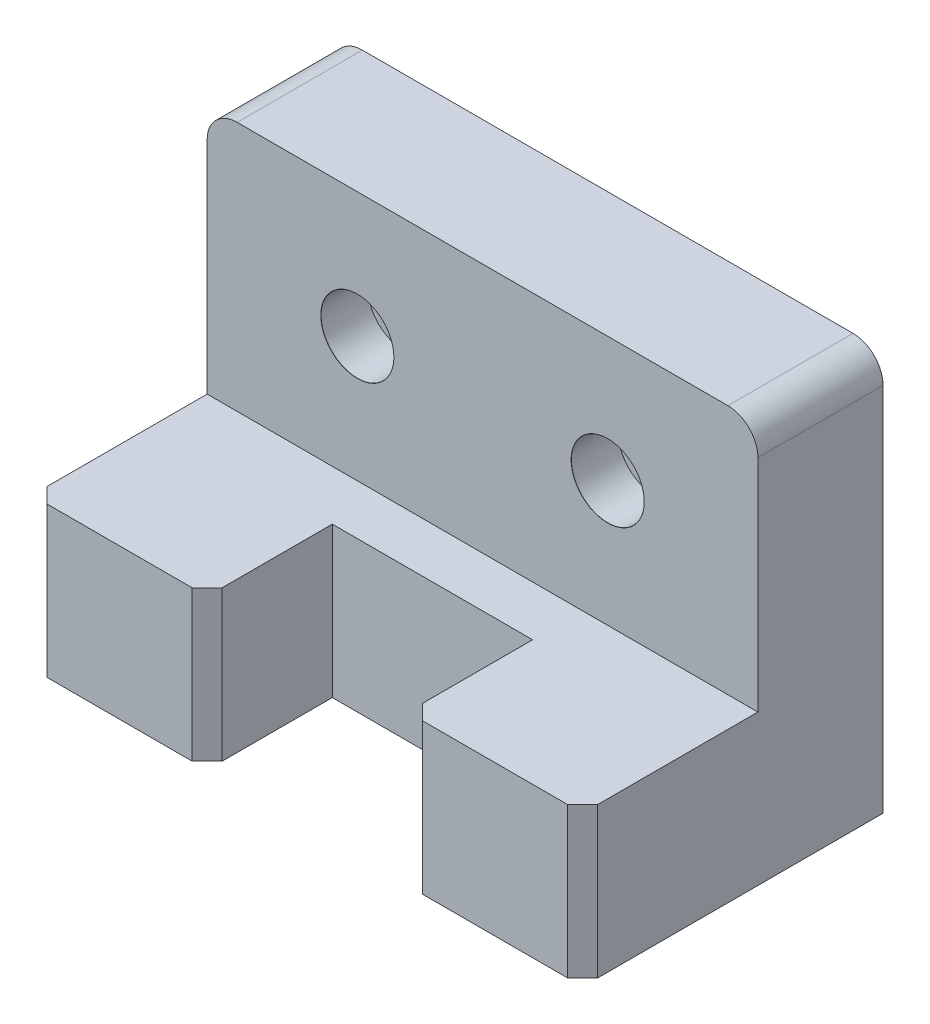
SolidWorks part; units mm, degrees
ref_plane "Front Plane" through (0, 0, 0) normal (0, 0, 1) x (1, 0, 0)
ref_plane "Top Plane" through (0, 0, 0) normal (0, 1, 0) x (1, 0, 0)
ref_plane "Right Plane" through (0, 0, 0) normal (1, 0, 0) x (0, 0, -1)
sketch "Sketch1" plane through (0, 0, 0) normal (0, 1, 0) x (1, 0, 0)
  line L0 (-20, -57) -> (-20, -35)
  line L1 (-55, 0) -> (55, 0)
  line L2 (-55, 0) -> (-55, -57)
  line L3 (-52, -60) -> (-23, -60)
  line L4 (55, 0) -> (55, -57)
  line L5 (-20, -35) -> (20, -35)
  line L6 (20, -35) -> (20, -57)
  line L7 (23, -60) -> (52, -60)
  line L8 (-55, -57) -> (-52, -60)
  line L9 (-23, -60) -> (-20, -57)
  line L10 (20, -57) -> (23, -60)
  line L11 (52, -60) -> (55, -57)
  point P1 (55, -60)
  point P2 (-55, -60)
  point P4 (-20, -60)
  point P9 (20, -60)
  dimension "D1" = 25
  dimension "D2" = 60
  dimension "D3" = 40
  dimension "D4" = 35
  dimension "D5" = 35
extrude "Boss-Extrude1" add sketch "Sketch1" along normal blind 80
sketch "Sketch2" plane through (0, 80, 0) normal (0, 1, 0) x (1, 0, 0)
  line L0 (55, 0) -> (-55, 0) construction
  line L1 (-64.3629, -25) -> (63.5311, -25)
  line L2 (-64.3629, -25) -> (-64.3629, -72.2064)
  line L3 (-64.3629, -72.2064) -> (63.5311, -72.2064)
  line L4 (63.5311, -25) -> (63.5311, -72.2064)
  dimension "D1" = 25
extrude "Cut-Extrude1" cut sketch "Sketch2" against normal offset from surface (50 mm away) 30 up to face at (0, 0, 44.8333)
fillet "Fillet1" radius 6 2 edges at (55, 80, 12.5) (-55, 80, 12.5)
hole_wizard "CBORE for M6 Hex Head Bolt1" positions "3DSketch1" profile "Sketch3" counterbore size "M6" standard "ANSI Metric" end condition through all
sketch3d "3DSketch1"
  line L0 (-55, 30, 25) -> (-55, 74, 25) construction
  line L2 (49, 80, 25) -> (-49, 80, 25) construction
  point P0 (-25, 55, 25)
  point P2 (25, 55, 25)
  point P9 (0, 0, 0)
  point P10 (-25, 43.0674, 25)
  dimension "D1" = 30
  dimension "D2" = 50
  dimension "D3" = 25
sketch "Sketch3" plane through (-25, 55, 25) normal (1, 0, 0) x (0, -1, 0)
  line L0 (0, 0) -> (0, 25)
  line L1 (0, 25) -> (3.2, 25)
  line L3 (3.2, 25) -> (3.2, 9.38)
  line L4 (7.275, 9.38) -> (3.2, 9.38)
  line L5 (7.275, 9.38) -> (7.275, 0.025)
  line L6 (7.275, 0.025) -> (7.3, 0)
  line L7 (7.3, 0) -> (0, 0)
  line L8 (-7.275, 0.025) -> (-7.3, 0) construction
  line L11 (0, -6.35) -> (0, 107.95) construction
  dimension "Thru Hole Dia." = 6.4
  dimension "Thru Hole Depth" = 25
  dimension "C'Bore Dia." = 14.55
  dimension "C'Bore Depth" = 9.38
  dimension "Near C'Sink Dia." = 14.6
  dimension "Near C'Sink Angle" = 90
